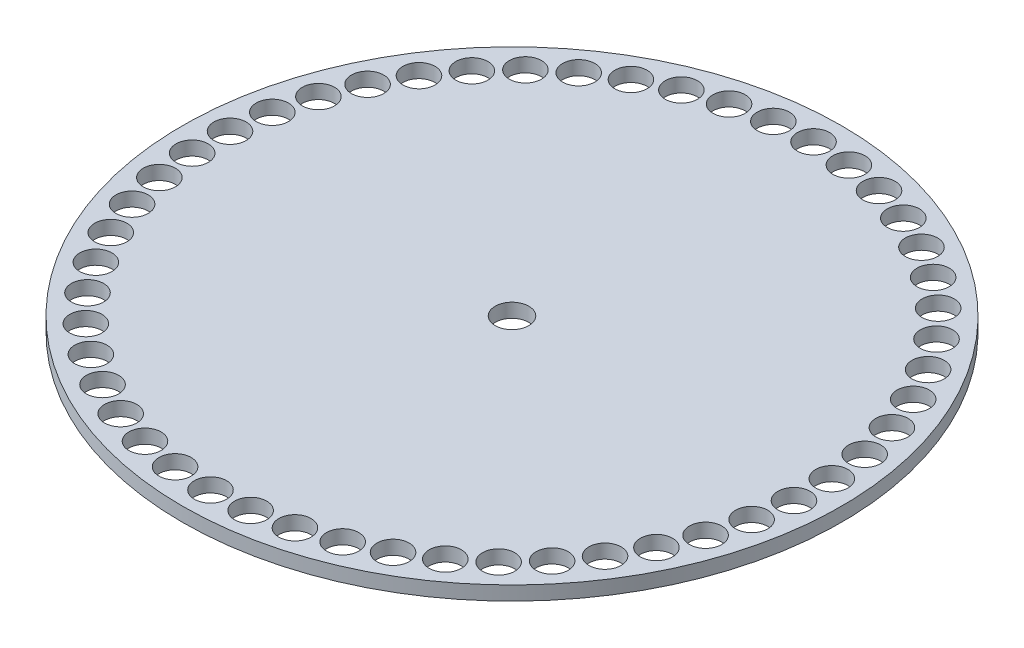
SolidWorks part; units mm, degrees
ref_plane "Front Plane" through (0, 0, 0) normal (0, 0, 1) x (1, 0, 0)
ref_plane "Top Plane" through (0, 0, 0) normal (0, 1, 0) x (1, 0, 0)
ref_plane "Right Plane" through (0, 0, 0) normal (1, 0, 0) x (0, 0, -1)
sketch "Sketch1" plane through (0, 0, 0) normal (0, 1, 0) x (1, 0, 0)
  circle A0 centre (0, 0) radius 117.5
  dimension "D1" = 235
extrude "Boss-Extrude1" add sketch "Sketch1" along normal blind 5
sketch "Sketch2" plane through (0, 5, 0) normal (0, 1, 0) x (1, 0, 0)
  line L0 (0, 0) -> (0, -117.5) construction
  circle A0 centre (0, 0) radius 117.5 construction
  circle A1 centre (0, 0) radius 107.5 construction
  circle A2 centre (0, 107.5) radius 5.75
  dimension "D1" = 215
  dimension "D2" = 11.5
extrude "Cut-Extrude1" cut sketch "Sketch2" against normal through all
pattern_circular "CirPattern1" count 50 over 360 about axis through (0, 0, 0) along (0, 1, 0) of "Cut-Extrude1"
sketch "Sketch3" plane through (0, 5, 0) normal (0, 1, 0) x (1, 0, 0)
  circle A0 centre (0, 0) radius 6
  dimension "D1" = 12
extrude "Cut-Extrude2" cut sketch "Sketch3" against normal through all
